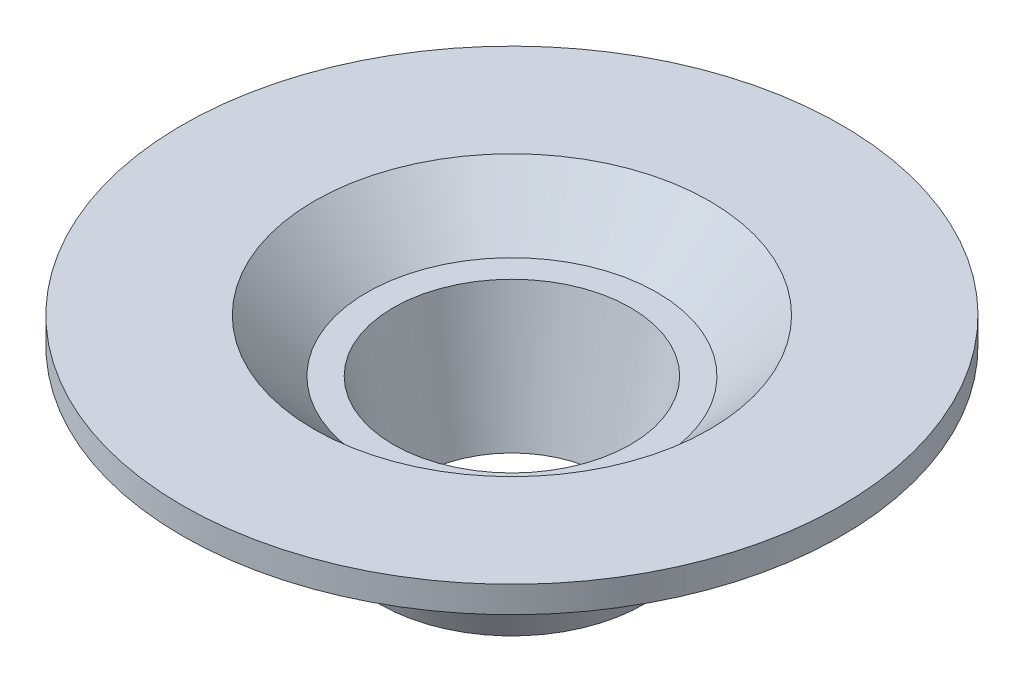
SolidWorks part; units mm, degrees
ref_plane "Front Plane" through (0, 0, 0) normal (0, 0, 1) x (1, 0, 0)
ref_plane "Top Plane" through (0, 0, 0) normal (0, 1, 0) x (1, 0, 0)
ref_plane "Right Plane" through (0, 0, 0) normal (1, 0, 0) x (0, 0, -1)
sketch "Sketch1" plane through (0, 0, 0) normal (1, 0, 0) x (0, 0, -1)
  line L0 (0, 0) -> (0, -5) construction
  line L1 (4.5, 0) -> (3.5, -5)
  line L2 (3.5, -5) -> (5, -5)
  line L3 (5, -5) -> (6.5, -1)
  line L4 (6.5, -1) -> (8.5, -1)
  line L5 (8.5, -1) -> (10.5, 1)
  line L6 (10.5, 1) -> (12.5, 1)
  line L7 (12.5, 1) -> (12.5, 2)
  line L8 (12.5, 2) -> (7.5, 2)
  line L9 (7.5, 2) -> (5.5, 0)
  line L10 (5.5, 0) -> (4.5, 0)
  dimension "D1" = 5
  dimension "D2" = 1.5
  dimension "D3" = 12.5
  dimension "D4" = 1
  dimension "D5" = 2
  dimension "D6" = 2
  dimension "D7" = 1
  dimension "D8" = 4.5
  dimension "D9" = 2
  dimension "D10" = 6.5
  dimension "D11" = 4
  dimension "D12" = 3.5
revolve "Revolve1" add sketch "Sketch1" angle 360 about L0
